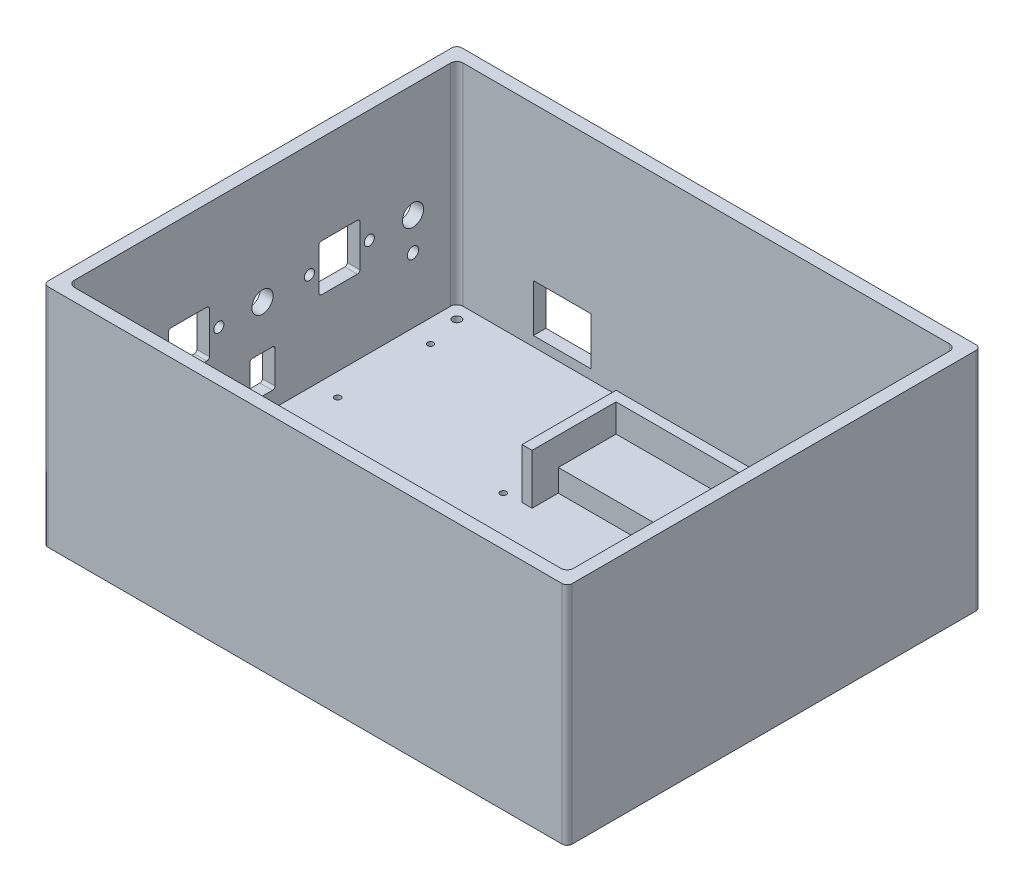
SolidWorks part; units mm, degrees
ref_plane "Alzado" through (0, 0, 0) normal (0, 0, 1) x (1, 0, 0)
ref_plane "Planta" through (0, 0, 0) normal (0, 1, 0) x (1, 0, 0)
ref_plane "Vista lateral" through (0, 0, 0) normal (1, 0, 0) x (0, 0, -1)
sketch "Croquis1" plane through (40.7521, -109.4, 0) normal (0, -1, 0) x (-1, 0, 0)
  line L0 (-162.6, -69.675) -> (-162.6, 69.675) construction
  line L1 (-254.3, -82.5) -> (-45.3, -82.5)
  line L2 (-254.3, -82.5) -> (-254.3, 82.5)
  line L3 (-254.3, 82.5) -> (-45.3, 82.5)
  line L4 (-45.3, -82.5) -> (-45.3, 82.5)
  line L5 (-254.3, -82.5) -> (-45.3, 82.5) construction
  line L6 (-254.3, 82.5) -> (-45.3, -82.5) construction
  line L7 (-136.3, 21.5) -> (-136.3, 55) construction
  line L8 (-246.3, 55) -> (-246.3, -55) construction
  point P0 (-149.8, 0)
  point P8 (-162.6, 0)
  dimension "D1" = 8
  dimension "D2" = 91
  dimension "D3" = 165
extrude "Saliente-Extruir1" add sketch "Croquis1" along normal blind 6
sketch "Croquis3" plane through (0, -109.4, 0) normal (0, 1, 0) x (1, 0, 0)
  line L0 (177.0521, -55) -> (177.0521, -21.5) construction
  line L1 (177.0521, 21.5) -> (177.0521, 55) construction
  line L2 (177.0521, 55) -> (287.0521, 55) construction
  line L3 (287.0521, 55) -> (287.0521, -55) construction
  line L12 (287.0521, -55) -> (177.0521, -55) construction
  line L13 (177.0521, -55) -> (177.0521, -21.5)
  line L14 (177.0521, 21.5) -> (177.0521, 55)
  line L15 (177.0521, 55) -> (287.0521, 55)
  line L16 (287.0521, 55) -> (287.0521, -55)
  line L17 (287.0521, -55) -> (177.0521, -55)
  line L18 (173.0521, 21.5) -> (173.0521, 59)
  line L19 (173.0521, 59) -> (291.0521, 59)
  line L20 (291.0521, 59) -> (291.0521, -59)
  line L21 (291.0521, -59) -> (173.0521, -59)
  line L22 (173.0521, -59) -> (173.0521, -21.5)
  line L23 (173.0521, -21.5) -> (177.0521, -21.5)
  line L24 (173.0521, 21.5) -> (177.0521, 21.5)
  dimension "D1" = 4
extrude "Saliente-Extruir2" add sketch "Croquis3" along normal blind 20
sketch "Croquis5" plane through (0, -109.4, 0) normal (0, 1, 0) x (1, 0, 0)
  line L0 (177.0521, 55) -> (287.0521, 55) construction
  line L1 (287.0521, -55) -> (177.0521, -55) construction
  line L2 (177.0521, 55) -> (287.0521, 55)
  line L3 (287.0521, -55) -> (177.0521, -55)
  line L4 (177.0521, 55) -> (177.0521, 31.9511)
  line L5 (177.0521, 21.5) -> (177.0521, 55) construction
  line L6 (177.0521, 31.9511) -> (287.0521, 31.9511)
  line L7 (287.0521, 55) -> (287.0521, -55) construction
  line L8 (287.0521, 31.9511) -> (287.0521, 55)
  line L9 (177.0521, -55) -> (177.0521, -31.9511)
  line L10 (177.0521, -31.9511) -> (287.0521, -31.9511)
  line L11 (287.0521, 55) -> (287.0521, -55) construction
  line L12 (287.0521, -31.9511) -> (287.0521, -55)
  dimension "D1" = 23.0489
extrude "Saliente-Extruir3" add sketch "Croquis5" along normal blind 8.865
sketch "Croquis6" plane through (0, -109.4, 0) normal (0, 1, 0) x (1, 0, 0)
  line L8 (91.0521, 77.5) -> (91.0521, -77.5)
  line L9 (91.0521, -77.5) -> (290.0521, -77.5)
  line L10 (290.0521, -77.5) -> (290.0521, 77.5)
  line L11 (290.0521, 77.5) -> (91.0521, 77.5)
  line L12 (91.0521, 77.5) -> (91.0521, -77.5)
  line L13 (91.0521, -77.5) -> (290.0521, -77.5)
  line L14 (290.0521, -77.5) -> (290.0521, 77.5)
  line L15 (290.0521, 77.5) -> (91.0521, 77.5)
  line L20 (86.0521, 82.5) -> (86.0521, -82.5)
  line L21 (86.0521, -82.5) -> (295.0521, -82.5)
  line L22 (295.0521, -82.5) -> (295.0521, 82.5)
  line L23 (295.0521, 82.5) -> (86.0521, 82.5)
  line L24 (86.0521, 82.5) -> (86.0521, -82.5)
  line L25 (86.0521, -82.5) -> (295.0521, -82.5)
  line L26 (295.0521, -82.5) -> (295.0521, 82.5)
  line L27 (295.0521, 82.5) -> (86.0521, 82.5)
  dimension "D1" = 5
  dimension "D2" = 0
extrude "Saliente-Extruir4" add sketch "Croquis6" along normal blind 84
sketch "Croquis8" plane through (0, 0, -82.5) normal (0, 0, -1) x (-1, 0, 0)
  line L0 (-144.5521, -86.5) -> (-121.5521, -86.5)
  line L1 (-144.5521, -86.5) -> (-144.5521, -105.5)
  line L3 (-121.5521, -105.5) -> (-121.5521, -86.5)
  line L4 (-96.0521, -86.5) -> (-170.0521, -86.5)
  line L5 (-170.0521, -86.5) -> (-170.0521, -109.4)
  line L6 (-170.0521, -109.4) -> (-96.0521, -109.4)
  line L7 (-96.0521, -109.4) -> (-96.0521, -86.5)
  line L8 (-96.0521, -86.5) -> (-170.0521, -86.5) construction
  line L9 (-170.0521, -86.5) -> (-170.0521, -109.4) construction
  line L10 (-170.0521, -109.4) -> (-96.0521, -109.4) construction
  line L11 (-96.0521, -109.4) -> (-96.0521, -86.5) construction
  line L16 (-144.5521, -105.5) -> (-121.5521, -105.5)
  point P7 (-133.0521, -86.5)
  dimension "D2" = 23
  dimension "D3" = 3.9
  dimension "D1" = 0
extrude "Cortar-Extruir2" cut sketch "Croquis8" against normal up to next
sketch "Croquis10" plane through (86.0521, 0, 0) normal (-1, 0, 0) x (0, 0, 1)
  line L0 (-82.5, -115.4) -> (-82.5, -25.4) construction
  line L1 (-82.5, -115.4) -> (-82.5, -25.4) construction
  line L2 (-82.5, -25.4) -> (82.5, -25.4) construction
  line L3 (-82.5, -25.4) -> (82.5, -25.4) construction
  line L5 (-5, -87.9) -> (5, -87.9)
  line L6 (-5, -87.9) -> (-5, -102.9)
  line L7 (-5, -102.9) -> (5, -102.9)
  line L8 (5, -87.9) -> (5, -102.9)
  line L9 (-5, -87.9) -> (5, -102.9) construction
  line L10 (-5, -102.9) -> (5, -87.9) construction
  circle A0 centre (0, -70.4) radius 1.25
  point P4 (0, -95.4)
  point P11 (0, -25.4)
  dimension "D4" = 2.5
  dimension "D1" = 10
  dimension "D2" = 15
  dimension "D3" = 0
  dimension "D5" = 70
  dimension "D6" = 17.5
extrude "Cortar-Extruir4" cut sketch "Croquis10" against normal up to next
sketch "Croquis9" plane through (86.0521, 0, 168.5521) normal (1, 0, 0) x (0, 0, -1)
  line L1 (191.0521, -79.7) -> (207.4021, -79.7)
  line L2 (86.0521, -115.4) -> (86.0521, -25.4) construction
  line L7 (191.0521, -79.7) -> (191.0521, -61.1)
  line L8 (191.0521, -61.1) -> (207.4021, -61.1)
  line L9 (86.0521, -115.4) -> (86.0521, -25.4) construction
  line L10 (207.4021, -79.7) -> (207.4021, -61.1)
  line L11 (191.0521, -79.7) -> (207.4021, -61.1) construction
  line L12 (191.0521, -61.1) -> (207.4021, -79.7) construction
  circle A0 centre (187.3021, -70.4) radius 2
  circle A1 centre (211.1521, -70.4) radius 2
  point P0 (199.2271, -70.4)
  point P3 (86.0521, -70.4)
  point P4 (199.2271, -70.4)
  dimension "D4" = 4
  dimension "D1" = 16.35
  dimension "D2" = 18.6
  dimension "D3" = 105
  dimension "D5" = 3.75
  dimension "D6" = 3.75
extrude "Cortar-Extruir5" cut sketch "Croquis9" along normal blind 10
hole_wizard "Taladro de margen para 5/161" positions "Croquis12" profile "Croquis14" hole size "5/16" standard "Ansi Inch"
sketch "Croquis12" plane through (86.0521, 0, 0) normal (-1, 0, 0) x (0, 0, 1)
  point P0 (0, -70.4)
sketch "Croquis14" plane through (86.0521, -70.4, 0) normal (0, 1, 0) x (0, 0, 1)
  line L0 (0, 0) -> (0, 23.7335)
  line L1 (0, 23.7335) -> (4.2164, 21.2)
  line L2 (4.2164, 21.2) -> (4.2164, 0)
  line L5 (4.2164, 0) -> (0, 0)
  line L10 (0, 23.7335) -> (-4.2164, 21.2) construction
  line L11 (0, -6.35) -> (0, 107.95) construction
  dimension "Diámetro de taladro" = 8.4328
  dimension "Profundidad de taladro" = 21.2
  dimension "Ángulo de perforador" = 118
sketch "Croquis15" plane through (0, -115.4, 0) normal (0, -1, 0) x (1, 0, 0)
  circle A0 centre (100.0521, -58) radius 1.2 construction
  circle A1 centre (166.0521, -58) radius 1.2 construction
  circle A2 centre (166.0521, -21) radius 1.2 construction
  circle A3 centre (100.0521, -21) radius 1.2 construction
  circle A4 centre (100.0521, -58) radius 1.2
  circle A5 centre (166.0521, -58) radius 1.2
  circle A6 centre (166.0521, -21) radius 1.2
  circle A7 centre (100.0521, -21) radius 1.2
hole_wizard "Avellanado para tornillo con cabeza plana de M21" positions "Croquis16" profile "Croquis18" countersink size "M2" standard "Ansi Metric" end condition through all
sketch "Croquis16" plane through (0, -115.4, 0) normal (0, -1, 0) x (-1, 0, 0)
  point P0 (-166.0521, 58)
  point P3 (-166.0521, 21)
  point P6 (-100.0521, 21)
  point P9 (-100.0521, 58)
sketch "Croquis18" plane through (166.0521, -115.4, -58) normal (1, 0, 0) x (0, 0, -1)
  line L0 (0, 0) -> (0, 90)
  line L1 (0, 90) -> (1.2, 90)
  line L2 (1.2, 90) -> (1.2, 1)
  line L3 (1.2, 1) -> (2.2, 0)
  line L5 (2.2, 0) -> (0, 0)
  line L6 (-1.2, 1) -> (-2.2, 0) construction
  line L11 (0, -6.35) -> (0, 107.95) construction
  dimension "Diámetro de taladro hasta el siguiente" = 2.4
  dimension "Profundidad de taladro hasta el siguiente" = 90
  dimension "Diámetro de avellanado cercano" = 4.4
  dimension "Ángulo de avellanado cercano" = 90
fillet "Redondeo1" radius 2 4 edges at (86.0521, -70.4, -82.5) (86.0521, -70.4, 82.5) (295.0521, -70.4, -82.5) (295.0521, -70.4, 82.5)
fillet "Redondeo2" radius 2.5 4 edges at (290.0521, -67.4, 77.5) (290.0521, -67.4, -77.5) (91.0521, -67.4, -77.5) (91.0521, -67.4, 77.5)
pattern_linear "MatrizL2" count 2 spacing 60 along (0, 0, -1) of "Taladro de margen para 5/161"
pattern_linear "MatrizL3" count 2 spacing 60 along (0, 0, 1) of "Cortar-Extruir5"
sketch "Croquis20" plane through (86.0521, 0, 0) normal (-1, 0, 0) x (0, 0, 1)
  line L0 (55.5, -73.4) -> (55.5, -67.4) construction
  line L1 (51.75, -73.4) -> (51.75, -67.4)
  line L2 (59.25, -73.4) -> (59.25, -67.4)
  line L3 (80.5, -115.4) -> (80.5, -25.4) construction
  arc A0 (51.75, -73.4) -> (59.25, -73.4) centre (55.5, -73.4) ccw
  arc A1 (59.25, -67.4) -> (51.75, -67.4) centre (55.5, -67.4) ccw
  point P2 (55.5, -70.4)
  point P10 (80.5, -70.4)
  dimension "D1" = 3.75
  dimension "D2" = 6
  dimension "D3" = 25
extrude "Cortar-Extruir6" cut sketch "Croquis20" against normal blind 10
sketch "Croquis21" plane through (0, -115.4, 0) normal (0, -1, 0) x (1, 0, 0)
  circle A0 centre (96.8021, 71.75) radius 2 construction
  circle A1 centre (96.8021, 71.75) radius 2
  circle A2 centre (96.8021, -71.75) radius 2 construction
  circle A3 centre (96.8021, -71.75) radius 2
  circle A4 centre (284.3021, 71.75) radius 2 construction
  circle A5 centre (284.3021, -71.75) radius 2 construction
  circle A6 centre (284.3021, 71.75) radius 2
  circle A7 centre (284.3021, -71.75) radius 2
hole_wizard "Refrentado para tornillo tapón con cabeza plana de clavija de M31" positions "Croquis22" profile "Croquis23" countersink size "M3" standard "Ansi Metric"
sketch "Croquis22" plane through (0, -115.4, 0) normal (0, -1, 0) x (-1, 0, 0)
  point P0 (-284.3021, 71.75)
  point P3 (-284.3021, -71.75)
  point P6 (-96.8021, -71.75)
  point P9 (-96.8021, 71.75)
sketch "Croquis23" plane through (284.3021, -115.4, -71.75) normal (1, 0, 0) x (0, 0, -1)
  line L0 (0, 0) -> (0, 9.2215)
  line L1 (0, 9.2215) -> (1.7, 8.2)
  line L2 (1.7, 8.2) -> (1.7, 1.66)
  line L3 (1.7, 1.66) -> (3.36, 0)
  line L5 (3.36, 0) -> (0, 0)
  line L6 (-1.7, 1.66) -> (-3.36, 0) construction
  line L10 (0, 9.2215) -> (-1.7, 8.2) construction
  line L11 (0, -6.35) -> (0, 107.95) construction
  dimension "Diámetro de taladro" = 3.4
  dimension "Profundidad de taladro" = 8.2
  dimension "Ángulo de avellanado cercano" = 6.72
  dimension "Ángulo de avellanado lejano" = 90
  dimension "Ángulo de perforador" = 118
sketch "Croquis24" plane through (86.0521, 0, 0) normal (-1, 0, 0) x (0, 0, 1)
  circle A0 centre (-60, -70.4) radius 4.2164 construction
  circle A2 centre (-60, -70.4) radius 4.2164 construction
  circle A3 centre (-60, -83.4) radius 2.25
  dimension "D1" = 4.5
  dimension "D2" = 13
extrude "Cortar-Extruir7" cut sketch "Croquis24" against normal up to next
fillet "Redondeo3" radius 1 12 edges at (88.5521, -87.9, 5) (88.5521, -87.9, -5) (88.5521, -102.9, 5) (88.5521, -102.9, -5) (88.5521, -61.1, 37.5) (88.5521, -79.7, 21.15) (88.5521, -61.1, 21.15) (88.5521, -79.7, 37.5) (88.5521, -79.7, -22.5) (88.5521, -61.1, -22.5) (88.5521, -61.1, -38.85) (88.5521, -79.7, -38.85)
